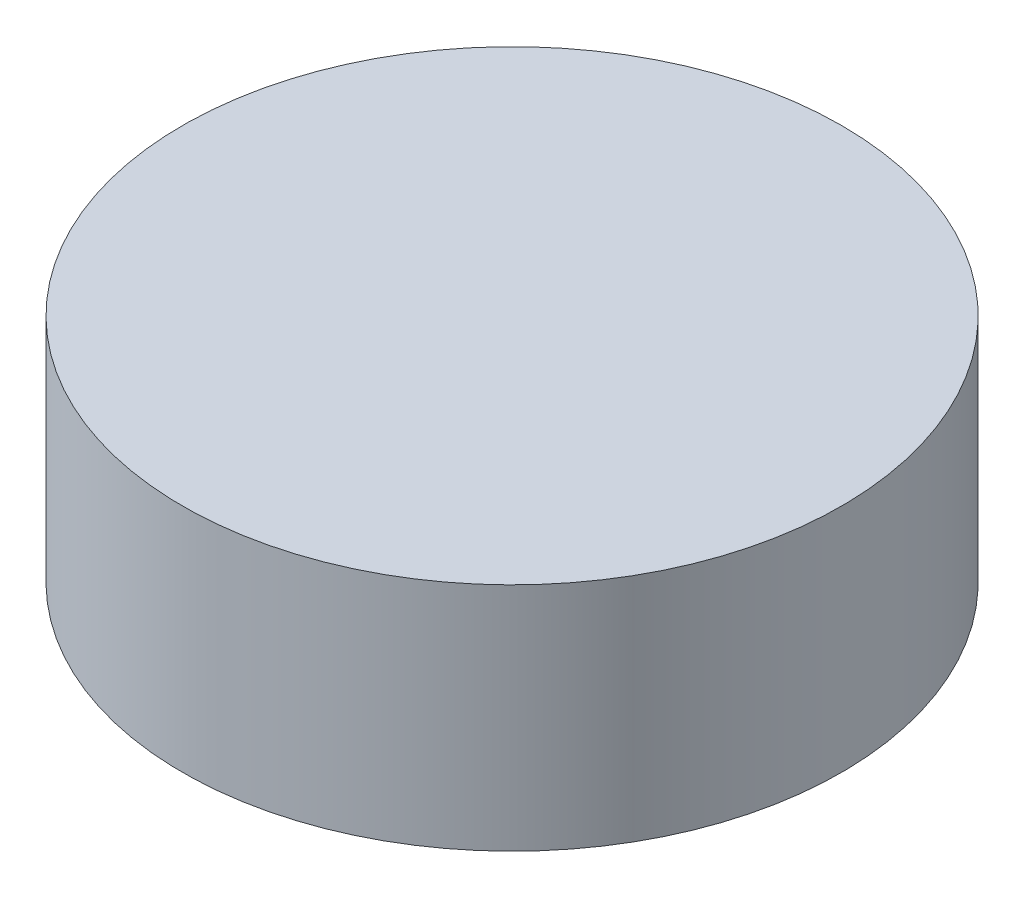
SolidWorks part; units mm, degrees
ref_plane "Alzado" through (0, 0, 0) normal (0, 0, 1) x (1, 0, 0)
ref_plane "Planta" through (0, 0, 0) normal (0, 1, 0) x (1, 0, 0)
ref_plane "Vista lateral" through (0, 0, 0) normal (1, 0, 0) x (0, 0, -1)
ref_plane "Plano_TacoPVC3" through (0, 18, 0) normal (0, 1, 0) x (1, 0, 0)
sketch "SkTacoPVC3" plane through (0, 18, 0) normal (0, 1, 0) x (1, 0, 0)
  circle A0 centre (-75, -129.9038) radius 20
extrude "TacoPVC3" add sketch "SkTacoPVC3" along normal blind 14 separate body
